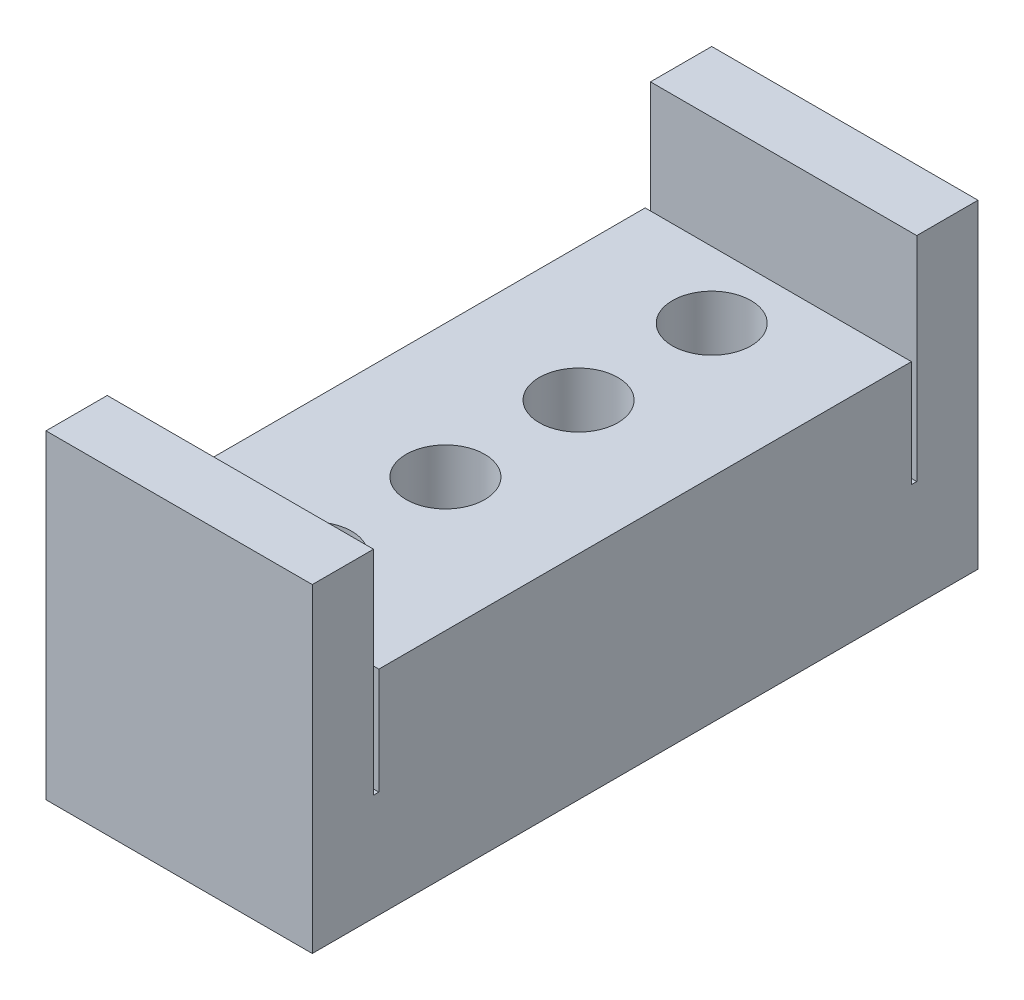
SolidWorks part; units mm, degrees
ref_plane "Front Plane" through (0, 0, 0) normal (0, 0, 1) x (1, 0, 0)
ref_plane "Top Plane" through (0, 0, 0) normal (0, 1, 0) x (1, 0, 0)
ref_plane "Right Plane" through (0, 0, 0) normal (1, 0, 0) x (0, 0, -1)
sketch "Sketch1" plane through (0, 0, 0) normal (0, 1, 0) x (1, 0, 0)
  line L1 (-5, 12.5) -> (5, 12.5)
  line L2 (-5, 12.5) -> (-5, -12.5)
  line L3 (-5, -12.5) -> (5, -12.5)
  line L4 (5, 12.5) -> (5, -12.5)
  line L5 (-5, 12.5) -> (5, -12.5) construction
  line L6 (-5, -12.5) -> (5, 12.5) construction
  point P0 (0, 0)
  dimension "D1" = 10
  dimension "D2" = 25
extrude "Boss-Extrude1" add sketch "Sketch1" along normal blind 8
sketch "Sketch8" plane through (0, 8, 0) normal (0, 1, 0) x (1, 0, 0)
  line L0 (5, -12.5) -> (5, 12.5) construction
  line L1 (-5, 12.5) -> (5, 12.5)
  line L2 (-5, 12.5) -> (-5, 10.2)
  line L3 (-5, 10.2) -> (5, 10.2)
  line L4 (5, 12.5) -> (5, 10.2)
  line L6 (-5, -12.5) -> (5, -12.5)
  line L7 (-5, -12.5) -> (-5, -10.2)
  line L8 (-5, -10.2) -> (5, -10.2)
  line L9 (5, -12.5) -> (5, -10.2)
  dimension "D1" = 20.4
extrude "Boss-Extrude4" add sketch "Sketch8" along normal blind 4
sketch "Sketch9" plane through (0, 8, 0) normal (0, 1, 0) x (1, 0, 0)
  line L0 (5, -10.2) -> (5, 10.2) construction
  line L1 (-5, 10.2) -> (5, 10.2)
  line L2 (-5, 10.2) -> (-5, 10)
  line L3 (-5, 10) -> (5, 10)
  line L4 (5, 10.2) -> (5, 10)
  line L6 (-5, -10.2) -> (5, -10.2)
  line L7 (-5, -10.2) -> (-5, -10)
  line L8 (-5, -10) -> (5, -10)
  line L9 (5, -10.2) -> (5, -10)
  dimension "D1" = 0.2
extrude "Cut-Extrude3" cut sketch "Sketch9" against normal blind 4
sketch "Sketch4" plane through (0, 0, 0) normal (0, -1, 0) x (1, 0, 0)
  circle A0 centre (0, 7.5) radius 1.475
  dimension "D1" = 2.95
  dimension "D2" = 7.5
extrude "Cut-Extrude2" cut sketch "Sketch4" against normal up to surface (8 mm away) up to face at (0, 8, 0)
pattern_linear "LPattern1" count 4 spacing 5 along (0, 0, -1) of "Cut-Extrude2"
